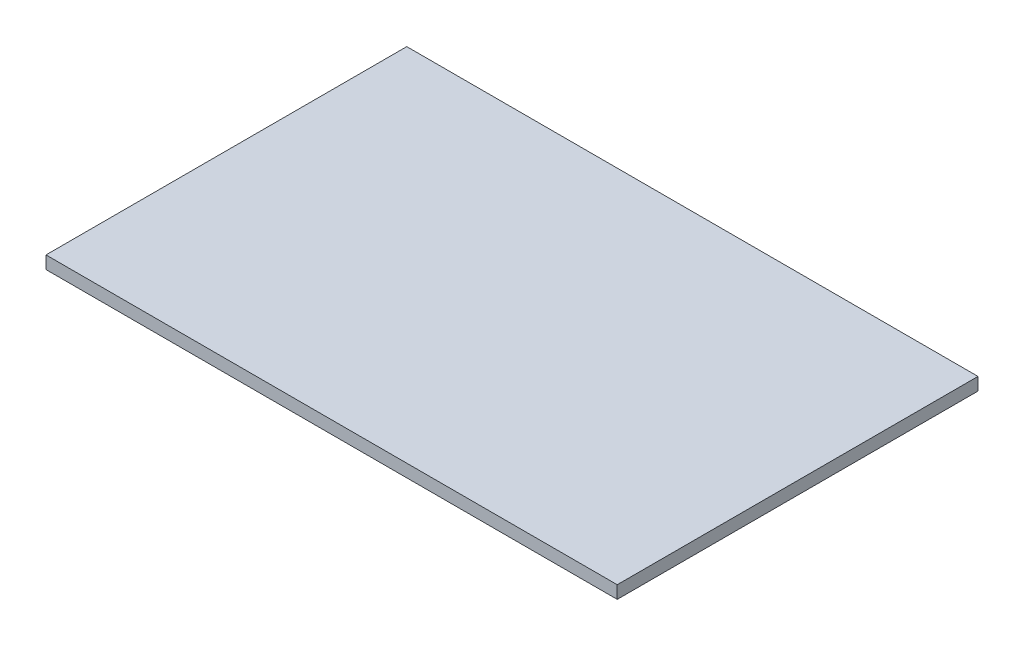
SolidWorks part; units mm, degrees
material "Oak"
ref_plane "Front Plane" through (0, 0, 0) normal (0, 0, 1) x (1, 0, 0)
ref_plane "Top Plane" through (0, 0, 0) normal (0, 1, 0) x (1, 0, 0)
ref_plane "Right Plane" through (0, 0, 0) normal (1, 0, 0) x (0, 0, -1)
sketch "Sketch1" plane through (0, 0, 0) normal (0, 1, 0) x (1, 0, 0)
  line L1 (0, 0) -> (784.225, 0)
  line L2 (0, 0) -> (0, 495.3)
  line L3 (0, 495.3) -> (784.225, 495.3)
  line L4 (784.225, 0) -> (784.225, 495.3)
  dimension "D1" = 495.3
  dimension "D2" = 784.225
extrude "Boss-Extrude1" add sketch "Sketch1" along normal blind 17.4625
